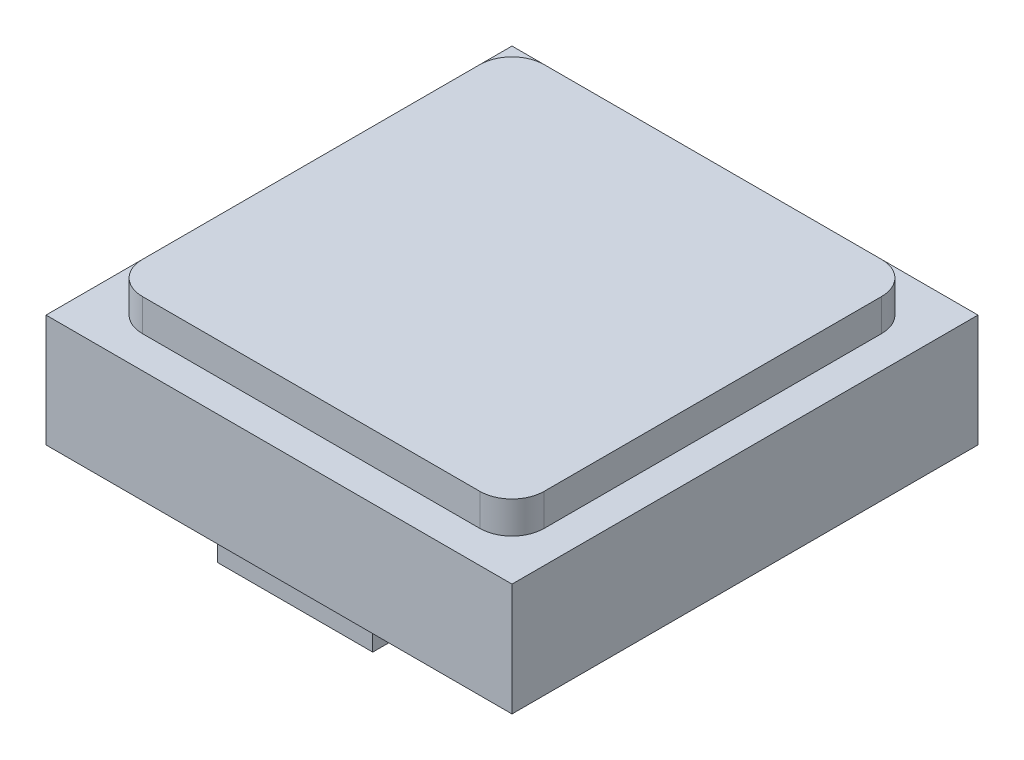
SolidWorks part; units mm, degrees
ref_plane "Front Plane" through (0, 0, 0) normal (0, 0, 1) x (1, 0, 0)
ref_plane "Top Plane" through (0, 0, 0) normal (0, 1, 0) x (1, 0, 0)
ref_plane "Right Plane" through (0, 0, 0) normal (1, 0, 0) x (0, 0, -1)
sketch "Sketch1" plane through (0, 0, 0) normal (0, 1, 0) x (1, 0, 0)
  line L1 (-14.5, 14.5) -> (14.5, 14.5)
  line L2 (-14.5, 14.5) -> (-14.5, -14.5)
  line L3 (-14.5, -14.5) -> (14.5, -14.5)
  line L4 (14.5, 14.5) -> (14.5, -14.5)
  line L5 (-14.5, 14.5) -> (14.5, -14.5) construction
  line L6 (-14.5, -14.5) -> (14.5, 14.5) construction
  point P0 (0, 0)
  dimension "D1" = 29
  dimension "D2" = 29
extrude "Boss-Extrude1" add sketch "Sketch1" along normal blind 11
sketch "Sketch2" plane through (0, 11, 0) normal (0, 1, 0) x (1, 0, 0)
  line L0 (14.5, 14.5) -> (-14.5, 14.5) construction
  line L1 (-10.5, 12.5) -> (10.5, 12.5)
  line L2 (-12.5, 10.5) -> (-12.5, -10.5)
  line L3 (-10.5, -12.5) -> (10.5, -12.5)
  line L4 (12.5, 10.5) -> (12.5, -10.5)
  line L5 (-14.5, 14.5) -> (-14.5, -14.5) construction
  line L6 (-14.5, -14.5) -> (14.5, -14.5) construction
  line L7 (14.5, -14.5) -> (14.5, 14.5) construction
  line L8 (-10.5, 17.5) -> (10.5, 17.5)
  line L9 (17.5, 10.5) -> (17.5, -10.5)
  line L10 (-10.5, -17.5) -> (10.5, -17.5)
  line L11 (-17.5, 10.5) -> (-17.5, -10.5)
  arc A0 (10.5, -12.5) -> (12.5, -10.5) centre (10.5, -10.5) ccw
  arc A1 (10.5, 12.5) -> (12.5, 10.5) centre (10.5, 10.5) cw
  arc A2 (-10.5, 12.5) -> (-12.5, 10.5) centre (-10.5, 10.5) ccw
  arc A3 (-12.5, -10.5) -> (-10.5, -12.5) centre (-10.5, -10.5) ccw
  arc A4 (10.5, 17.5) -> (17.5, 10.5) centre (10.5, 10.5) cw
  arc A5 (10.5, -17.5) -> (17.5, -10.5) centre (10.5, -10.5) ccw
  arc A6 (-17.5, -10.5) -> (-10.5, -17.5) centre (-10.5, -10.5) ccw
  arc A7 (-10.5, 17.5) -> (-17.5, 10.5) centre (-10.5, 10.5) ccw
  dimension "D5" = 2
  dimension "D1" = 2
  dimension "D2" = 2
  dimension "D3" = 2
  dimension "D4" = 2
  dimension "D6" = 5
extrude "Cut-Extrude1" cut sketch "Sketch2" against normal blind 2
sketch "Sketch3" plane through (0, 0, 0) normal (0, -1, 0) x (-1, 0, 0)
  line L0 (-14.5, 14.5) -> (14.5, 14.5) construction
  line L1 (-12.5, 12.5) -> (12.5, 12.5)
  line L2 (-12.5, 12.5) -> (-12.5, -5.5)
  line L3 (-12.5, -5.5) -> (12.5, -5.5)
  line L4 (12.5, 12.5) -> (12.5, -5.5)
  line L5 (-14.5, -14.5) -> (-14.5, 14.5) construction
  line L6 (14.5, 14.5) -> (14.5, -14.5) construction
  line L8 (-14.5, 14.5) -> (14.5, 14.5)
  line L9 (-14.5, 14.5) -> (-14.5, -14.5)
  line L10 (-14.5, -14.5) -> (14.5, -14.5)
  line L11 (14.5, 14.5) -> (14.5, -14.5)
  dimension "D1" = 20
  dimension "D2" = 2
  dimension "D3" = 2
  dimension "D4" = 2
extrude "Cut-Extrude2" cut sketch "Sketch3" against normal blind 2
sketch "Sketch4" plane through (0, 2, 0) normal (0, -1, 0) x (1, 0, 0)
  line L0 (14.5, 12.9234) -> (4.8333, 12.9234) construction
  line L1 (4.8333, 9.5) -> (-4.8333, 9.5)
  line L2 (4.8333, 9.5) -> (4.8333, 13.5)
  line L3 (4.8333, 13.5) -> (-4.8333, 13.5)
  line L4 (-4.8333, 9.5) -> (-4.8333, 13.5)
  line L5 (14.5, -14.5) -> (14.5, 14.5) construction
  line L6 (-4.8333, 11.5) -> (-14.5, 11.5) construction
  line L7 (-14.5, 14.5) -> (-14.5, -14.5) construction
  line L8 (14.5, 14.5) -> (-14.5, 14.5) construction
  dimension "D1" = 1
  dimension "D2" = 4
extrude "Boss-Extrude2" add sketch "Sketch4" along normal blind 2
ref_plane "Mid-Plane" through (0, 0, 0) normal (-1, 0, 0) x (0, 0, 1)
